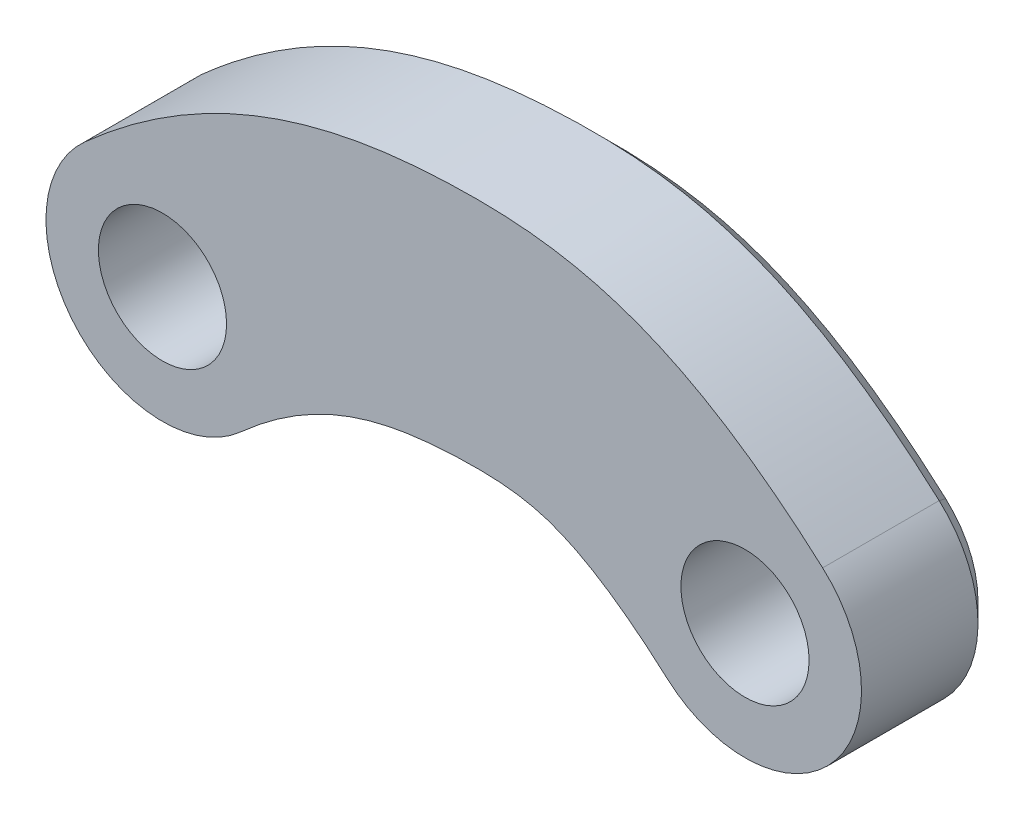
SolidWorks part; units mm, degrees
ref_plane "前视基准面" through (0, 0, 0) normal (0, 0, 1) x (1, 0, 0)
ref_plane "上视基准面" through (0, 0, 0) normal (0, 1, 0) x (1, 0, 0)
ref_plane "右视基准面" through (0, 0, 0) normal (1, 0, 0) x (0, 0, -1)
sketch "草图1" plane through (0, 0, 0) normal (0, 0, 1) x (1, 0, 0)
  line L0 (0, 0) -> (15, 0) construction
  circle A0 centre (0, 0) radius 1.65
  circle A1 centre (15, 0) radius 1.65
  arc A2 (-2, 2.2361) -> (3, 0) centre (0, 0) ccw
  arc A3 (12, 0) -> (17, 2.2361) centre (15, 0) ccw
  spline S0 degree 3 poles (-2, 2.2361) (1.2984, 5.1862) (7.705, 6.6305) (13.2917, 5.5529) (17, 2.2361) knots 0 0 0 0 0.5 1 1 1 1
  spline S1 degree 1 poles (2, -2.2361) (13, -2.2361) knots 0 0 1 1 construction
  spline S2 degree 3 poles (2, -2.2361) (2.1332, -2.1169) (2.4132, -1.8778) (2.9289, -1.4785) (3.5383, -1.075) (4.214, -0.719) (5.0756, -0.3686) (5.9402, -0.155) (6.8886, -0.0356) (7.6916, 0.0102) (8.4448, 0.0117) (9.0231, -0.0331) (9.5179, -0.1183) (9.9915, -0.253) (10.5261, -0.4715) (11.1809, -0.8271) (11.8607, -1.2925) (12.4783, -1.7812) (12.8327, -2.0864) (13, -2.2361) knots 0 0 0 0 0.03125 0.0625 0.125 0.1875 0.25 0.375 0.4375 0.5 0.5625 0.625 0.6875 0.75 0.8125 0.875 0.9375 0.96875 1 1 1 1
  point P9 (7.5, 0)
  dimension "D2" = 3.3
  dimension "D3" = 3.3
  dimension "D4" = 6
  dimension "D5" = 6
  dimension "D1" = 15
  dimension "D6" = 6
  dimension "D7" = 9.5
  dimension "D8" = 9.5
  dimension "D9" = 6
extrude "凸台-拉伸2" add sketch "草图1" along normal blind 3.5
chamfer "倒角1" distance 0.5 angle 45 4 edges at (-2.2361, -2, 0) (17.2361, -2, 0)
